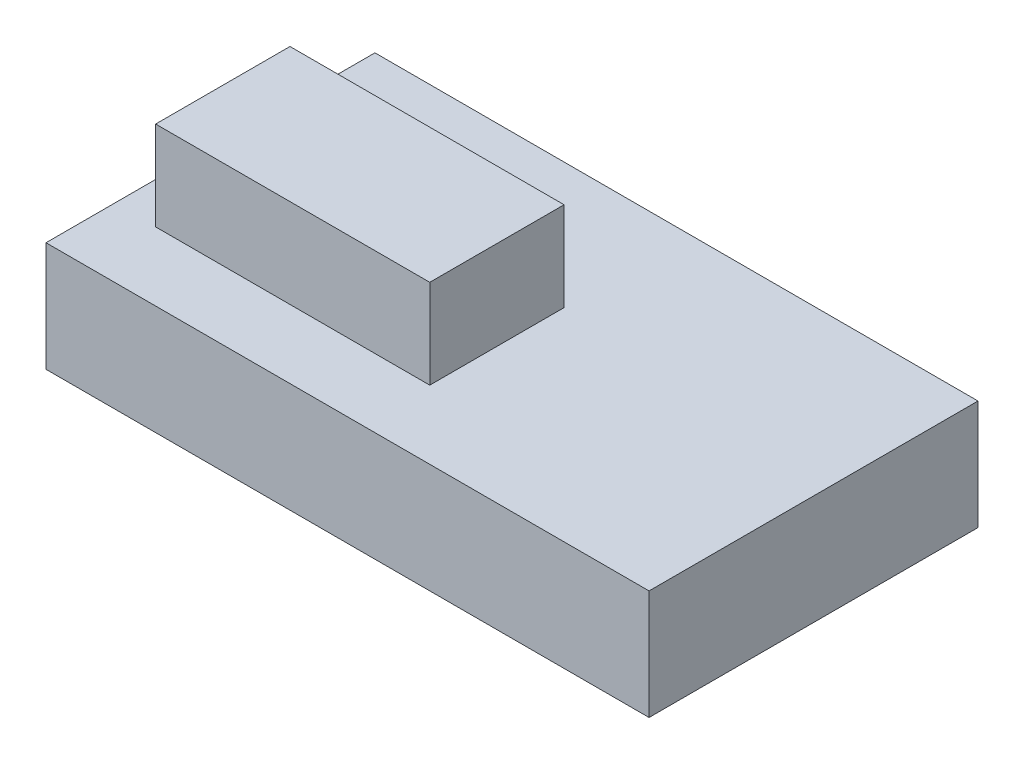
SolidWorks part; units mm, degrees
ref_plane "Front Plane" through (0, 0, 0) normal (0, 0, 1) x (1, 0, 0)
ref_plane "Top Plane" through (0, 0, 0) normal (0, 1, 0) x (1, 0, 0)
ref_plane "Right Plane" through (0, 0, 0) normal (1, 0, 0) x (0, 0, -1)
sketch "Sketch1" plane through (0, 0, 0) normal (0, 1, 0) x (1, 0, 0)
  line L1 (0, 0) -> (-55.88, 0)
  line L2 (0, 0) -> (0, 30.48)
  line L3 (0, 30.48) -> (-55.88, 30.48)
  line L4 (-55.88, 0) -> (-55.88, 30.48)
  dimension "D1" = 30.48
  dimension "D2" = 55.88
extrude "Boss-Extrude1" add sketch "Sketch1" along normal blind 10.16
sketch "Sketch2" plane through (0, 10.16, 0) normal (0, 1, 0) x (1, 0, 0)
  line L0 (0, 0) -> (0, 30.48) construction
  line L1 (-52.07, 6.35) -> (-26.67, 6.35)
  line L2 (-52.07, 6.35) -> (-52.07, 18.796)
  line L3 (-52.07, 18.796) -> (-26.67, 18.796)
  line L4 (-26.67, 6.35) -> (-26.67, 18.796)
  line L5 (-55.88, 0) -> (0, 0) construction
  dimension "D1" = 26.67
  dimension "D2" = 6.35
  dimension "D3" = 12.446
  dimension "D4" = 25.4
extrude "Boss-Extrude2" add sketch "Sketch2" along normal blind 8.255
